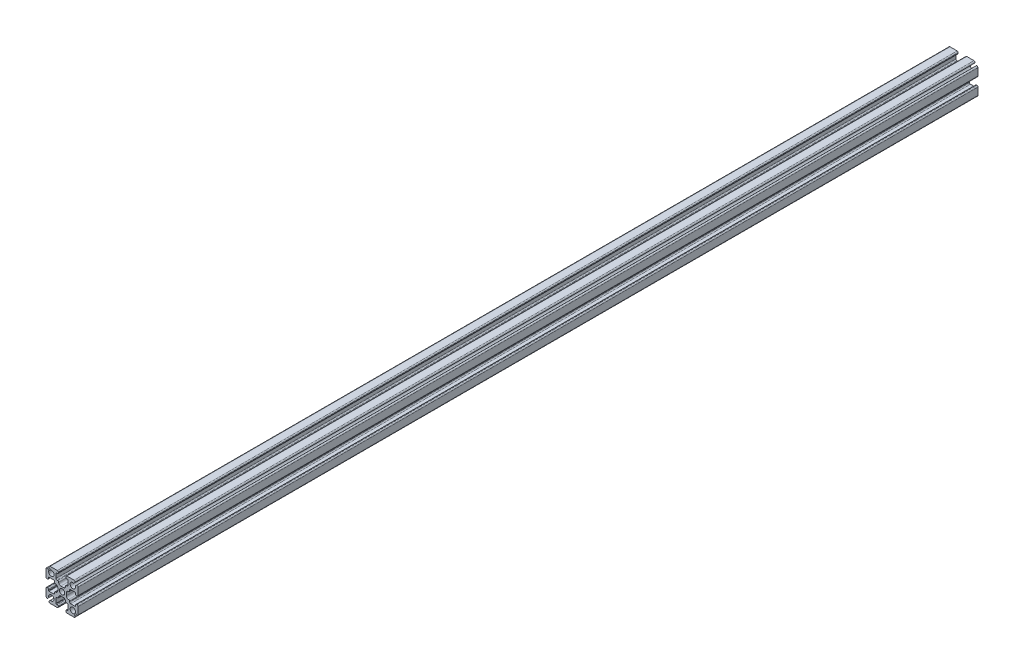
SolidWorks part; units mm, degrees
ref_plane "Front Plane" through (0, 0, 0) normal (0, 0, 1) x (1, 0, 0)
ref_plane "Top Plane" through (0, 0, 0) normal (0, 1, 0) x (1, 0, 0)
ref_plane "Right Plane" through (0, 0, 0) normal (1, 0, 0) x (0, 0, -1)
ref_plane "Plane1" through (0, 0, 0) normal (0, 0, -1) x (-1, 0, 0)
sketch "Sketch1" plane through (0, 0, 0) normal (0, 0, -1) x (-1, 0, 0)
  line L0 (6.6464, 5.9393) -> (6.1636, 5.4565)
  line L1 (5.4565, 6.1636) -> (5.9393, 6.6464)
  line L2 (5.5858, 7.5) -> (2.25, 7.5)
  line L3 (1.75, 7) -> (1.75, 6.8)
  line L4 (2.25, 6.3) -> (2.65, 6.3)
  line L5 (2.85, 6.1) -> (2.85, 4)
  line L6 (2.35, 3.5) -> (2.1, 3.5)
  line L7 (0.6, 2) -> (-0.6, 2)
  line L8 (-2.1, 3.5) -> (-2.35, 3.5)
  line L9 (-2.85, 4) -> (-2.85, 6.1)
  line L10 (-2.65, 6.3) -> (-2.25, 6.3)
  line L11 (-1.75, 6.8) -> (-1.75, 7)
  line L12 (-2.25, 7.5) -> (-5.5858, 7.5)
  line L13 (-5.9393, 6.6464) -> (-5.4565, 6.1636)
  line L14 (-6.1636, 5.4565) -> (-6.6464, 5.9393)
  line L15 (-7.5, 5.5858) -> (-7.5, 2.25)
  line L16 (-7, 1.75) -> (-6.8, 1.75)
  line L17 (-6.3, 2.25) -> (-6.3, 2.65)
  line L18 (-6.1, 2.85) -> (-4, 2.85)
  line L19 (-3.5, 2.35) -> (-3.5, 2.1)
  line L20 (-2, 0.6) -> (-2, -0.6)
  line L21 (-3.5, -2.1) -> (-3.5, -2.35)
  line L22 (-4, -2.85) -> (-6.1, -2.85)
  line L23 (-6.3, -2.65) -> (-6.3, -2.25)
  line L24 (-6.8, -1.75) -> (-7, -1.75)
  line L25 (-7.5, -2.25) -> (-7.5, -5.5858)
  line L26 (-6.6464, -5.9393) -> (-6.1636, -5.4565)
  line L27 (-5.4565, -6.1636) -> (-5.9393, -6.6464)
  line L28 (-5.5858, -7.5) -> (-2.25, -7.5)
  line L29 (-1.75, -7) -> (-1.75, -6.8)
  line L30 (-2.25, -6.3) -> (-2.65, -6.3)
  line L31 (-2.85, -6.1) -> (-2.85, -4)
  line L32 (-2.35, -3.5) -> (-2.1, -3.5)
  line L33 (-0.6, -2) -> (0.6, -2)
  line L34 (2.1, -3.5) -> (2.35, -3.5)
  line L35 (2.85, -4) -> (2.85, -6.1)
  line L36 (2.65, -6.3) -> (2.25, -6.3)
  line L37 (1.75, -6.8) -> (1.75, -7)
  line L38 (2.25, -7.5) -> (5.5858, -7.5)
  line L39 (5.9393, -6.6464) -> (5.4565, -6.1636)
  line L40 (6.1636, -5.4565) -> (6.6464, -5.9393)
  line L41 (7.5, -5.5858) -> (7.5, -2.25)
  line L42 (7, -1.75) -> (6.8, -1.75)
  line L43 (6.3, -2.25) -> (6.3, -2.65)
  line L44 (6.1, -2.85) -> (4, -2.85)
  line L45 (3.5, -2.35) -> (3.5, -2.1)
  line L46 (2, -0.6) -> (2, 0.6)
  line L47 (3.5, 2.1) -> (3.5, 2.35)
  line L48 (4, 2.85) -> (6.1, 2.85)
  line L49 (6.3, 2.65) -> (6.3, 2.25)
  line L50 (6.8, 1.75) -> (7, 1.75)
  line L51 (7.5, 2.25) -> (7.5, 5.5858)
  circle A0 centre (0, 0) radius 1.25
  arc A1 (6.1636, 5.4565) -> (5.4565, 6.1636) centre (5, 5) cw
  arc A2 (5.9393, 6.6464) -> (5.5858, 7.5) centre (5.5858, 7) ccw
  arc A3 (2.25, 7.5) -> (1.75, 7) centre (2.25, 7) ccw
  arc A4 (1.75, 6.8) -> (2.25, 6.3) centre (2.25, 6.8) ccw
  arc A5 (2.65, 6.3) -> (2.85, 6.1) centre (2.65, 6.1) cw
  arc A6 (2.85, 4) -> (2.35, 3.5) centre (2.35, 4) cw
  arc A7 (2.1, 3.5) -> (1.6, 3) centre (2.1, 3) ccw
  arc A8 (1.6, 3) -> (0.6, 2) centre (0.6, 3) cw
  arc A9 (-0.6, 2) -> (-1.6, 3) centre (-0.6, 3) cw
  arc A10 (-1.6, 3) -> (-2.1, 3.5) centre (-2.1, 3) ccw
  arc A11 (-2.35, 3.5) -> (-2.85, 4) centre (-2.35, 4) cw
  arc A12 (-2.85, 6.1) -> (-2.65, 6.3) centre (-2.65, 6.1) cw
  arc A13 (-2.25, 6.3) -> (-1.75, 6.8) centre (-2.25, 6.8) ccw
  arc A14 (-1.75, 7) -> (-2.25, 7.5) centre (-2.25, 7) ccw
  arc A15 (-5.5858, 7.5) -> (-5.9393, 6.6464) centre (-5.5858, 7) ccw
  arc A16 (-5.4565, 6.1636) -> (-6.1636, 5.4565) centre (-5, 5) cw
  arc A17 (-6.6464, 5.9393) -> (-7.5, 5.5858) centre (-7, 5.5858) ccw
  arc A18 (-7.5, 2.25) -> (-7, 1.75) centre (-7, 2.25) ccw
  arc A19 (-6.8, 1.75) -> (-6.3, 2.25) centre (-6.8, 2.25) ccw
  arc A20 (-6.3, 2.65) -> (-6.1, 2.85) centre (-6.1, 2.65) cw
  arc A21 (-4, 2.85) -> (-3.5, 2.35) centre (-4, 2.35) cw
  arc A22 (-3.5, 2.1) -> (-3, 1.6) centre (-3, 2.1) ccw
  arc A23 (-3, 1.6) -> (-2, 0.6) centre (-3, 0.6) cw
  arc A24 (-2, -0.6) -> (-3, -1.6) centre (-3, -0.6) cw
  arc A25 (-3, -1.6) -> (-3.5, -2.1) centre (-3, -2.1) ccw
  arc A26 (-3.5, -2.35) -> (-4, -2.85) centre (-4, -2.35) cw
  arc A27 (-6.1, -2.85) -> (-6.3, -2.65) centre (-6.1, -2.65) cw
  arc A28 (-6.3, -2.25) -> (-6.8, -1.75) centre (-6.8, -2.25) ccw
  arc A29 (-7, -1.75) -> (-7.5, -2.25) centre (-7, -2.25) ccw
  arc A30 (-7.5, -5.5858) -> (-6.6464, -5.9393) centre (-7, -5.5858) ccw
  arc A31 (-6.1636, -5.4565) -> (-5.4565, -6.1636) centre (-5, -5) cw
  arc A32 (-5.9393, -6.6464) -> (-5.5858, -7.5) centre (-5.5858, -7) ccw
  arc A33 (-2.25, -7.5) -> (-1.75, -7) centre (-2.25, -7) ccw
  arc A34 (-1.75, -6.8) -> (-2.25, -6.3) centre (-2.25, -6.8) ccw
  arc A35 (-2.65, -6.3) -> (-2.85, -6.1) centre (-2.65, -6.1) cw
  arc A36 (-2.85, -4) -> (-2.35, -3.5) centre (-2.35, -4) cw
  arc A37 (-2.1, -3.5) -> (-1.6, -3) centre (-2.1, -3) ccw
  arc A38 (-1.6, -3) -> (-0.6, -2) centre (-0.6, -3) cw
  arc A39 (0.6, -2) -> (1.6, -3) centre (0.6, -3) cw
  arc A40 (1.6, -3) -> (2.1, -3.5) centre (2.1, -3) ccw
  arc A41 (2.35, -3.5) -> (2.85, -4) centre (2.35, -4) cw
  arc A42 (2.85, -6.1) -> (2.65, -6.3) centre (2.65, -6.1) cw
  arc A43 (2.25, -6.3) -> (1.75, -6.8) centre (2.25, -6.8) ccw
  arc A44 (1.75, -7) -> (2.25, -7.5) centre (2.25, -7) ccw
  arc A45 (5.5858, -7.5) -> (5.9393, -6.6464) centre (5.5858, -7) ccw
  arc A46 (5.4565, -6.1636) -> (6.1636, -5.4565) centre (5, -5) cw
  arc A47 (6.6464, -5.9393) -> (7.5, -5.5858) centre (7, -5.5858) ccw
  arc A48 (7.5, -2.25) -> (7, -1.75) centre (7, -2.25) ccw
  arc A49 (6.8, -1.75) -> (6.3, -2.25) centre (6.8, -2.25) ccw
  arc A50 (6.3, -2.65) -> (6.1, -2.85) centre (6.1, -2.65) cw
  arc A51 (4, -2.85) -> (3.5, -2.35) centre (4, -2.35) cw
  arc A52 (3.5, -2.1) -> (3, -1.6) centre (3, -2.1) ccw
  arc A53 (3, -1.6) -> (2, -0.6) centre (3, -0.6) cw
  arc A54 (2, 0.6) -> (3, 1.6) centre (3, 0.6) cw
  arc A55 (3, 1.6) -> (3.5, 2.1) centre (3, 2.1) ccw
  arc A56 (3.5, 2.35) -> (4, 2.85) centre (4, 2.35) cw
  arc A57 (6.1, 2.85) -> (6.3, 2.65) centre (6.1, 2.65) cw
  arc A58 (6.3, 2.25) -> (6.8, 1.75) centre (6.8, 2.25) ccw
  arc A59 (7, 1.75) -> (7.5, 2.25) centre (7, 2.25) ccw
  arc A60 (7.5, 5.5858) -> (6.6464, 5.9393) centre (7, 5.5858) ccw
extrude "Boss-Extrude1" add sketch "Sketch1" against normal blind 420
